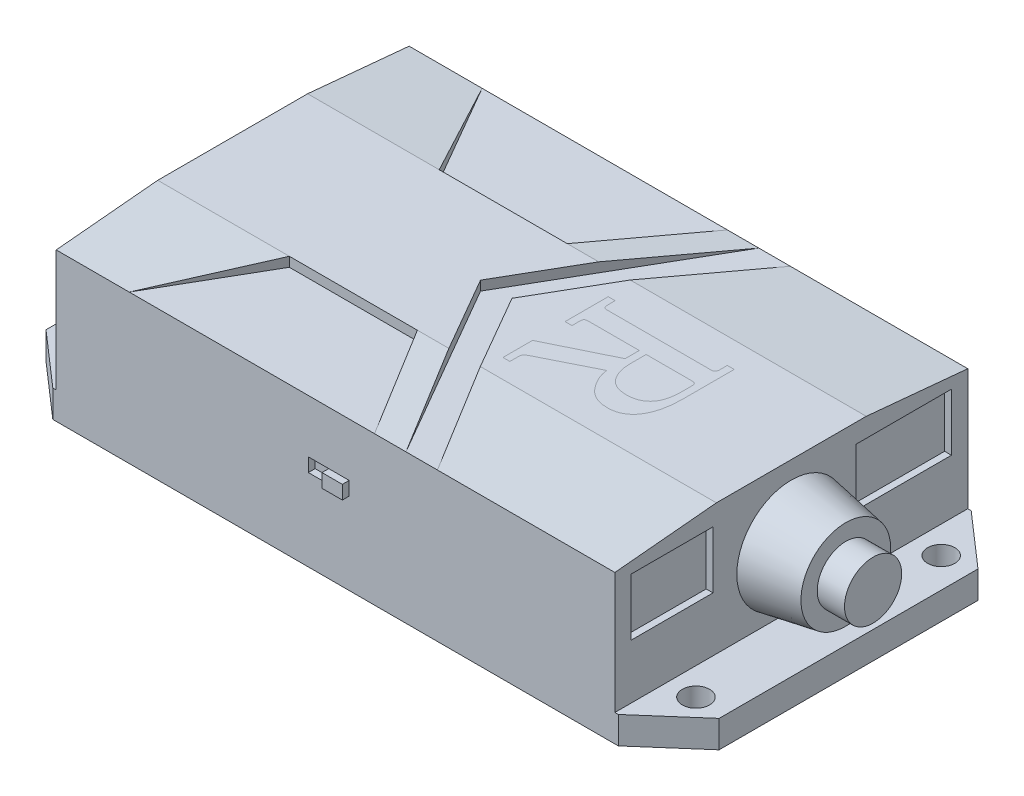
SolidWorks part; units mm, degrees
ref_plane "前视基准面" through (0, 0, 0) normal (0, 0, 1) x (1, 0, 0)
ref_plane "上视基准面" through (0, 0, 0) normal (0, 1, 0) x (1, 0, 0)
ref_plane "右视基准面" through (0, 0, 0) normal (1, 0, 0) x (0, 0, -1)
sketch "草图1" plane through (0, 0, 0) normal (0, 1, 0) x (1, 0, 0)
  line L0 (-24.7, 0) -> (24.7, 0) construction
  line L1 (-20.75, 12.95) -> (20.75, 12.95)
  line L2 (20.75, 12.95) -> (24.7, 9.5)
  line L3 (24.7, 9.5) -> (24.7, -9.5)
  line L4 (24.7, -9.5) -> (20.75, -12.95)
  line L5 (20.75, -12.95) -> (-20.75, -12.95)
  line L6 (-20.75, -12.95) -> (-24.7, -9.5)
  line L7 (-24.7, -9.5) -> (-24.7, 9.5)
  line L8 (-24.7, 9.5) -> (-20.75, 12.95)
  line L9 (0, -12.95) -> (0, 12.95) construction
  line L11 (-22.5, -9) -> (22.5, -9) construction
  line L12 (-22.5, -9) -> (-22.5, 9) construction
  line L13 (-22.5, 9) -> (22.5, 9) construction
  line L14 (22.5, -9) -> (22.5, 9) construction
  line L15 (-22.5, -9) -> (22.5, 9) construction
  line L16 (-22.5, 9) -> (22.5, -9) construction
  circle A0 centre (22.5, 9) radius 1
  circle A1 centre (22.5, -9) radius 1
  circle A2 centre (-22.5, -9) radius 1
  circle A3 centre (-22.5, 9) radius 1
  point P3 (0, 0)
  point P6 (24.7, 0)
  point P13 (0, 0)
  point P15 (-24.7, 0)
  dimension "D5" = 2
  dimension "D1" = 25.9
  dimension "D2" = 49.4
  dimension "D3" = 19
  dimension "D4" = 41.5
  dimension "D6" = 45
  dimension "D7" = 18
extrude "凸台-拉伸1" add sketch "草图1" along normal blind 2
sketch "草图2" plane through (0, 2, 0) normal (0, 1, 0) x (1, 0, 0)
  line L0 (20.75, 12.95) -> (-20.75, 12.95) construction
  line L1 (-20.5, -12.95) -> (20.5, -12.95)
  line L2 (-20.5, -12.95) -> (-20.5, 12.95)
  line L3 (-20.5, 12.95) -> (20.5, 12.95)
  line L4 (20.5, -12.95) -> (20.5, 12.95)
  line L5 (-20.5, -12.95) -> (20.5, 12.95) construction
  line L6 (-20.5, 12.95) -> (20.5, -12.95) construction
  point P0 (0, 0)
  dimension "D1" = 41
extrude "凸台-拉伸2" add sketch "草图2" along normal blind 9.6
sketch "草图3" plane through (20.5, 0, 0) normal (1, 0, 0) x (0, 0, -1)
  line L0 (-5.5, 11.6) -> (-12.95, 10.9)
  line L1 (-12.95, 11.6) -> (12.95, 11.6) construction
  line L2 (-12.95, 11.6) -> (-12.95, 2) construction
  line L3 (-12.95, 10.9) -> (-12.95, 11.6)
  line L4 (-12.95, 11.6) -> (-5.5, 11.6)
  line L5 (0, 0) -> (0, 11.6) construction
  line L6 (12.95, 11.6) -> (5.5, 11.6)
  line L7 (12.95, 10.9) -> (12.95, 11.6)
  line L8 (5.5, 11.6) -> (12.95, 10.9)
  dimension "D1" = 11
  dimension "D2" = 10.9
extrude "切除-拉伸1" cut sketch "草图3" against normal through all
sketch "草图4" plane through (0, 11.6, 0) normal (0, 1, 0) x (1, 0, 0)
  line L0 (7.4767, 12.95) -> (0, 0)
  line L1 (-20.5, 12.95) -> (20.5, 12.95) construction
  line L2 (0, 0) -> (7.4767, -12.95)
  line L3 (-20.5, -12.95) -> (20.5, -12.95) construction
  line L4 (5.1673, 12.95) -> (-2.3094, 0)
  line L5 (-2.3094, 0) -> (5.1673, -12.95)
  line L6 (2.8579, 12.95) -> (-1.4434, 5.5)
  line L7 (-1.4434, -5.5) -> (2.8579, -12.95)
  line L8 (-6.1421, 12.95) -> (-6.1421, -12.95) construction
  line L9 (-1.4434, 5.5) -> (-10.8409, 5.5)
  line L10 (20.5, 5.5) -> (-20.5, 5.5) construction
  line L11 (-1.4434, -5.5) -> (-10.8409, -5.5)
  line L12 (-20.5, -5.5) -> (20.5, -5.5) construction
  line L13 (7.4767, -12.95) -> (5.1673, -12.95)
  line L14 (7.4767, 12.95) -> (5.1673, 12.95)
  line L15 (2.8579, 12.95) -> (-15.1421, 12.95)
  line L16 (2.8579, -12.95) -> (-15.1421, -12.95)
  line L17 (-2.3094, 0) -> (5.7446, -13.95) construction
  line L18 (-4.6188, 0) -> (4.0126, -14.95) construction
  line L19 (4.0126, 14.95) -> (-4.6188, 0) construction
  line L20 (5.7446, 13.95) -> (-2.3094, 0) construction
  line L21 (-10.8409, -5.5) -> (-15.1421, -12.95)
  line L22 (-15.1421, 12.95) -> (-10.8409, 5.5)
  line L23 (0, 0) -> (20.5, 0) construction
  line L24 (20.5, -5.5) -> (20.5, 5.5) construction
  point P31 (-6.1421, -5.5)
  point P32 (-6.1421, 5.5)
  dimension "D3" = 120
  dimension "D4" = 18
  dimension "D1" = 2
  dimension "D2" = 2
extrude "切除-拉伸2" cut sketch "草图4" against normal blind 0.7
sketch "草图5" plane through (-20.5, 0, 0) normal (-1, 0, 0) x (0, 0, 1)
  line L0 (-4, 3.5) -> (4, 3.5) construction
  line L1 (-9.5, 0) -> (9.5, 0) construction
  circle A0 centre (0, 3.5) radius 1.25
  circle A1 centre (4, 3.5) radius 1.25
  circle A2 centre (-4, 3.5) radius 1.25
  point P6 (0, 3.5)
  dimension "D2" = 2.5
  dimension "D1" = 8
  dimension "D3" = 3.5
extrude "凸台-拉伸3" add sketch "草图5" along normal blind 2
sketch "草图6" plane through (20.5, 0, 0) normal (1, 0, 0) x (0, 0, -1)
  line L0 (-9.5, 0) -> (9.5, 0) construction
  circle A0 centre (0, 6.3) radius 4
  dimension "D1" = 8
  dimension "D2" = 6.3
extrude "凸台-拉伸4" add sketch "草图6" along normal blind 4 draft 10
sketch "草图7" plane through (24.5, 0, 0) normal (1, 0, 0) x (0, 0, -1)
  circle A0 centre (0, 6.3) radius 2.1
  dimension "D1" = 4.2
extrude "凸台-拉伸5" add sketch "草图7" along normal blind 2
sketch "草图8" plane through (-20.5, 0, 0) normal (-1, 0, 0) x (0, 0, 1)
  line L0 (-9.5, 0) -> (9.5, 0) construction
  line L1 (-6, 6) -> (6, 6)
  line L2 (-6, 6) -> (-6, 10.5)
  line L3 (-6, 10.5) -> (6, 10.5)
  line L4 (6, 6) -> (6, 10.5)
  line L5 (-6, 6) -> (6, 10.5) construction
  line L6 (-6, 10.5) -> (6, 6) construction
  point P0 (0, 8.25)
  dimension "D1" = 12
  dimension "D2" = 4.5
  dimension "D3" = 6
extrude "切除-拉伸3" cut sketch "草图8" against normal blind 0.5
sketch "草图9" plane through (20.5, 0, 0) normal (1, 0, 0) x (0, 0, -1)
  line L0 (-9.5, 0) -> (9.5, 0) construction
  line L1 (4.75, 10.2) -> (11.75, 10.2)
  line L2 (4.75, 10.2) -> (4.75, 6)
  line L3 (4.75, 6) -> (11.75, 6)
  line L4 (11.75, 10.2) -> (11.75, 6)
  line L5 (-11.75, 10.2) -> (-5.75, 10.2)
  line L6 (-11.75, 10.2) -> (-11.75, 6)
  line L7 (-11.75, 6) -> (-5.75, 6)
  line L8 (-5.75, 10.2) -> (-5.75, 6)
  line L9 (12.95, 10.9) -> (12.95, 2) construction
  line L10 (-12.95, 10.9) -> (-12.95, 2) construction
  dimension "D1" = 4.2
  dimension "D2" = 6
  dimension "D3" = 7
  dimension "D4" = 6
  dimension "D5" = 1.2
  dimension "D6" = 1.2
extrude "切除-拉伸4" cut sketch "草图9" against normal blind 0.5
sketch "草图11" plane through (0, 11.6, 0) normal (0, 1, 0) x (1, 0, 0)
  line L0 (3.1754, 5.5) -> (3.1754, -5.4544) construction
  text T0 "R" font "隶书" height in points 36
split line "分割线1"
sketch "草图12" plane through (0, 0, 12.95) normal (0, 0, 1) x (1, 0, 0)
  line L0 (-20.75, 0) -> (20.75, 0) construction
  line L1 (-2, 7) -> (1, 7)
  line L2 (-2, 7) -> (-2, 6)
  line L3 (-2, 6) -> (1, 6)
  line L4 (1, 7) -> (1, 6)
  line L5 (20.5, 10.9) -> (20.5, 2) construction
  dimension "D1" = 6
  dimension "D2" = 1
  dimension "D3" = 3
  dimension "D4" = 19.5
extrude "切除-拉伸5" cut sketch "草图12" against normal blind 0.5
sketch "草图13" plane through (0, 0, 12.45) normal (0, 0, 1) x (1, 0, 0)
  line L0 (-2, 6) -> (1, 6) construction
  line L1 (1, 7) -> (-0.5, 7)
  line L2 (1, 7) -> (1, 6)
  line L3 (1, 6) -> (-0.5, 6)
  line L4 (-0.5, 7) -> (-0.5, 6)
extrude "凸台-拉伸6" add sketch "草图13" along normal blind 1
